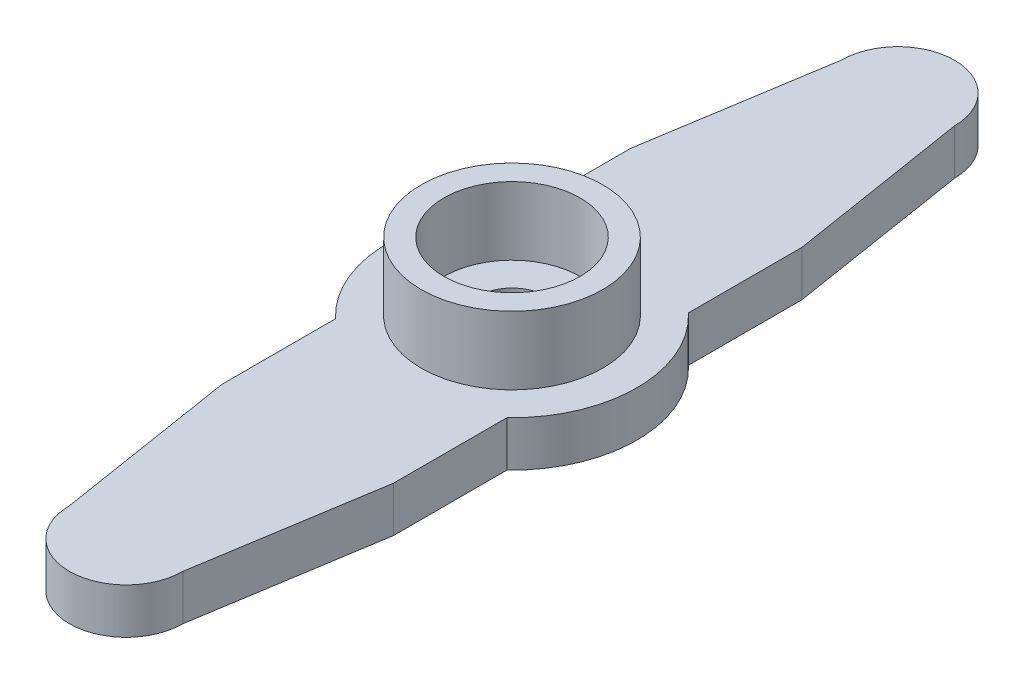
SolidWorks part; units mm, degrees
ref_plane "Front Plane" through (0, 0, 0) normal (0, 0, 1) x (1, 0, 0)
ref_plane "Top Plane" through (0, 0, 0) normal (0, 1, 0) x (1, 0, 0)
ref_plane "Right Plane" through (0, 0, 0) normal (1, 0, 0) x (0, 0, -1)
sketch "Sketch1" plane through (0, 0, 0) normal (0, 1, 0) x (1, 0, 0)
  line L0 (0, 0) -> (0, 13.0233) construction
  line L1 (-3.7749, 4) -> (3.7749, 4)
  line L2 (-3.7749, 4) -> (-3.7749, 9)
  line L3 (3.7749, 4) -> (3.7749, 9)
  line L4 (-3.7749, 9) -> (-2.5, 17)
  line L5 (3.7749, 9) -> (2.5, 17)
  line L6 (-23.3218, 0) -> (23.3218, 0) construction
  line L7 (-3.7749, -4) -> (3.7749, -4)
  line L8 (-3.7749, -4) -> (-3.7749, -9)
  line L9 (3.7749, -4) -> (3.7749, -9)
  line L10 (3.7749, -9) -> (2.5, -17)
  line L11 (-3.7749, -9) -> (-2.5, -17)
  circle A0 centre (0, 0) radius 1.5
  circle A1 centre (0, 0) radius 5.5
  arc A2 (-2.5, 17) -> (2.5, 17) centre (0, 17) cw
  arc A3 (-2.5, -17) -> (2.5, -17) centre (0, -17) ccw
  point P15 (0, 0)
  point P22 (0, 19.5)
  point P23 (0, -19.5)
  dimension "D1" = 11
  dimension "D2" = 3
  dimension "D7" = 2.5
  dimension "D3" = 4
  dimension "D4" = 5
  dimension "D5" = 8
  dimension "D6" = 8
  dimension "D8" = 39
extrude "Boss-Extrude1" add sketch "Sketch1" along normal blind 2 contours A2 L4 L2 A1 L3 L5 | L7 A1 L1 A0 | L1 A1 | L7 A1 | L11 A3 L10 L9 A1 L8
sketch "Sketch2" plane through (0, 2, 0) normal (0, 1, 0) x (1, 0, 0)
  circle A0 centre (0, 0) radius 4
  circle A1 centre (0, 0) radius 3
  dimension "D1" = 8
  dimension "D2" = 6
extrude "Boss-Extrude2" add sketch "Sketch2" along normal blind 3
